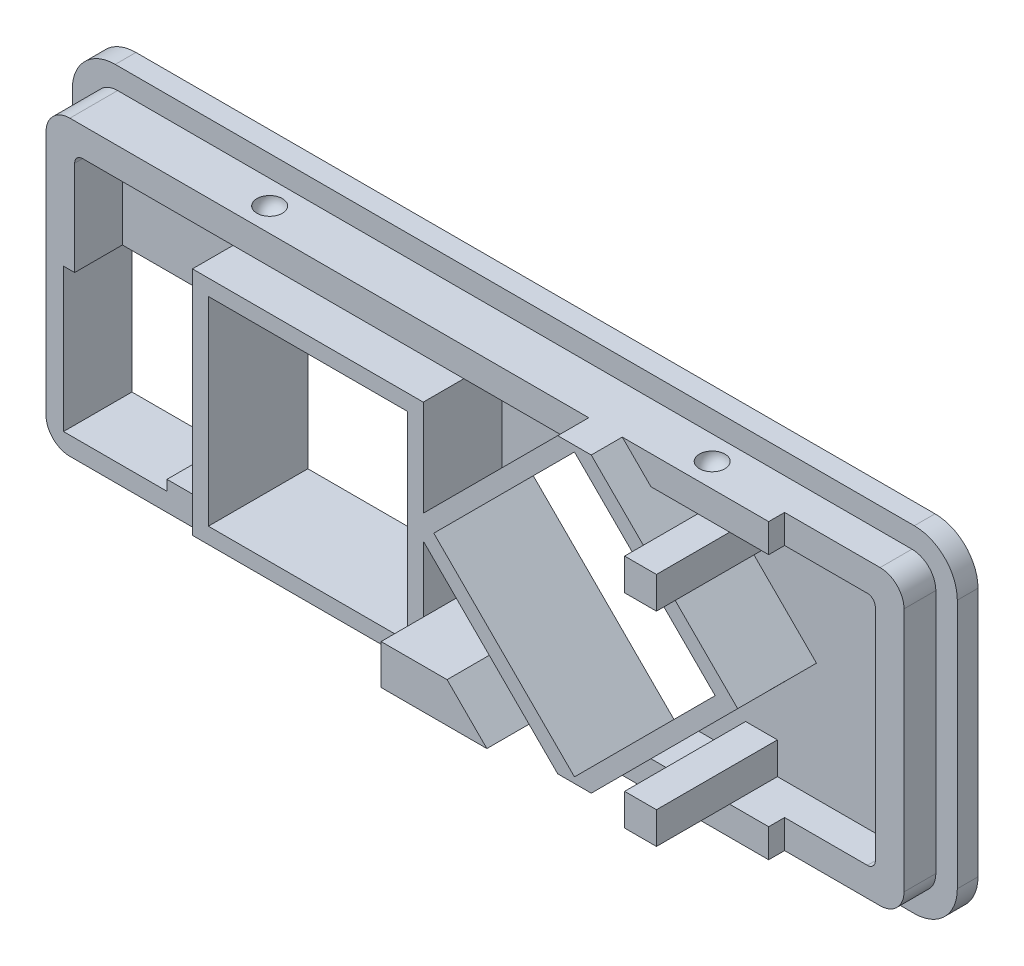
SolidWorks part; units mm, degrees
material "PLA"
ref_plane "Front Plane" through (0, 0, 0) normal (0, 0, 1) x (1, 0, 0)
ref_plane "Top Plane" through (0, 0, 0) normal (0, 1, 0) x (1, 0, 0)
ref_plane "Right Plane" through (0, 0, 0) normal (1, 0, 0) x (0, 0, -1)
sketch "Sketch1" plane through (0, 0, 0) normal (0, 0, 1) x (1, 0, 0)
  line L1 (2.7, 0) -> (52.9, 0)
  line L2 (0, 2.7) -> (0, 18.4)
  line L3 (2.7, 21.1) -> (52.9, 21.1)
  line L4 (55.6, 2.7) -> (55.6, 18.4)
  arc A0 (52.9, 0) -> (55.6, 2.7) centre (52.9, 2.7) ccw
  arc A1 (2.7, 0) -> (0, 2.7) centre (2.7, 2.7) cw
  arc A2 (0, 18.4) -> (2.7, 21.1) centre (2.7, 18.4) cw
  arc A3 (52.9, 21.1) -> (55.6, 18.4) centre (52.9, 18.4) cw
  point P9 (0, 0)
  dimension "D1" = 2.7
  dimension "D2" = 50.2
  dimension "D3" = 15.7
extrude "Boss-Extrude1" add sketch "Sketch1" along normal blind 1.3
sketch "Sketch4" plane through (0, 0, 1.3) normal (0, 0, 1) x (1, 0, 0)
  line L11 (54.25, 2.7) -> (54.25, 18.4)
  line L12 (52.9, 19.75) -> (2.7, 19.75)
  line L13 (1.35, 18.4) -> (1.35, 2.7)
  line L14 (2.7, 1.35) -> (52.9, 1.35)
  line L15 (54.25, 2.85) -> (54.25, 18.25)
  line L16 (52.75, 19.75) -> (2.85, 19.75)
  line L17 (1.35, 18.25) -> (1.35, 2.85)
  line L18 (2.85, 1.35) -> (52.75, 1.35)
  arc A4 (54.25, 18.25) -> (52.75, 19.75) centre (52.75, 18.25) ccw
  arc A5 (54.25, 2.85) -> (52.75, 1.35) centre (52.75, 2.85) cw
  arc A6 (1.35, 2.85) -> (2.85, 1.35) centre (2.85, 2.85) ccw
  arc A7 (2.85, 19.75) -> (1.35, 18.25) centre (2.85, 18.25) ccw
  arc A8 (52.9, 1.35) -> (54.25, 2.7) centre (52.9, 2.7) ccw
  arc A10 (54.25, 18.4) -> (52.9, 19.75) centre (52.9, 18.4) ccw
  arc A12 (2.7, 19.75) -> (1.35, 18.4) centre (2.7, 18.4) ccw
  arc A14 (1.35, 2.7) -> (2.7, 1.35) centre (2.7, 2.7) ccw
  dimension "D2" = 1.5
  dimension "D1" = 1.35
extrude "Boss-Extrude3" add sketch "Sketch4" along normal blind 3
sketch "Sketch5" plane through (0, 0, 4.3) normal (0, 0, 1) x (1, 0, 0)
  line L8 (52.45, 17.95) -> (3.15, 17.95)
  line L9 (3.15, 17.95) -> (3.15, 3.15)
  line L10 (3.15, 3.15) -> (52.45, 3.15)
  line L11 (52.45, 3.15) -> (52.45, 17.95)
  line L12 (51.95, 17.95) -> (3.65, 17.95)
  line L13 (3.15, 17.45) -> (3.15, 3.65)
  line L14 (3.65, 3.15) -> (51.95, 3.15)
  line L15 (52.45, 3.65) -> (52.45, 17.45)
  arc A4 (51.95, 3.15) -> (52.45, 3.65) centre (51.95, 3.65) ccw
  arc A5 (51.95, 17.95) -> (52.45, 17.45) centre (51.95, 17.45) cw
  arc A6 (3.65, 17.95) -> (3.15, 17.45) centre (3.65, 17.45) ccw
  arc A7 (3.15, 3.65) -> (3.65, 3.15) centre (3.65, 3.65) ccw
  dimension "D2" = 0.5
  dimension "D1" = 1.8
extrude "Cut-Extrude1" cut sketch "Sketch5" against normal blind 3
sketch "Sketch10" plane through (0, 19.75, 0) normal (0, 1, 0) x (1, 0, 0)
  line L0 (41.7, -2) -> (41.7, -3.6)
  line L1 (41.7, -3.6) -> (42.6713, -3.8888)
  line L3 (52.75, -1.3) -> (2.85, -1.3) construction
  line L4 (55.6, -1.3) -> (55.6, 0) construction
  arc A0 (41.7, -2) -> (41.7, -3.6) centre (41.7, -2.8) ccw
  dimension "D2" = 0.8
  dimension "D1" = 1.6
  dimension "D3" = 1.5
  dimension "D4" = 13.9
revolve "Cut-Revolve1" cut sketch "Sketch10" angle 360 about L0
ref_plane "Plane1" through (0, 10.55, 0) normal (0, -1, 0) x (-1, 0, 0)
mirror "Mirror1" about plane through (0, 10.55, 0) normal (0, -1, 0) of "Cut-Revolve1"
sketch "Sketch11" plane through (0, 0, 0) normal (0, 0, -1) x (-1, 0, 0)
  line L0 (0, 18.4) -> (0, 2.7) construction
  line L1 (-2.45, 2.5) -> (-8.95, 2.5)
  line L2 (-2.45, 2.5) -> (-2.45, 11.5)
  line L3 (-2.45, 11.5) -> (-8.95, 11.5)
  line L4 (-8.95, 2.5) -> (-8.95, 11.5)
  line L5 (-2.45, 2.5) -> (-8.95, 11.5) construction
  line L6 (-2.45, 11.5) -> (-8.95, 2.5) construction
  line L8 (-2.7, 0) -> (-52.9, 0) construction
  point P0 (-5.7, 7)
  dimension "D1" = 5.7
  dimension "D2" = 2.5
  dimension "D3" = 9
  dimension "D4" = 6.5
extrude "Cut-Extrude2" cut sketch "Sketch11" against normal blind 4.3
sketch "Sketch12" plane through (0, 0, 0) normal (0, 0, -1) x (-1, 0, 0)
  line L1 (-26, 16.35) -> (-13.5, 16.35)
  line L2 (-26, 16.35) -> (-26, 3.85)
  line L3 (-26, 3.85) -> (-13.5, 3.85)
  line L4 (-13.5, 16.35) -> (-13.5, 3.85)
  line L5 (-26, 16.35) -> (-13.5, 3.85) construction
  line L6 (-26, 3.85) -> (-13.5, 16.35) construction
  line L7 (-52.9, 21.1) -> (-2.7, 21.1) construction
  line L9 (0, 18.4) -> (0, 2.7) construction
  point P0 (-19.75, 10.1)
  dimension "D1" = 11
  dimension "D2" = 19.75
  dimension "D3" = 12.5
  dimension "D4" = 12.5
sketch "Sketch13" plane through (0, 0, 0) normal (0, 0, -1) x (-1, 0, 0)
  line L0 (-45.3388, 10.55) -> (-36.5, 1.7112)
  line L1 (-45.3388, 10.55) -> (-36.5, 19.3888)
  line L2 (-36.5, 1.7112) -> (-27.6612, 10.55)
  line L3 (-36.5, 19.3888) -> (-27.6612, 10.55)
  line L4 (-45.3388, 10.55) -> (-27.6612, 10.55) construction
  line L5 (-36.5, 1.7112) -> (-36.5, 19.3888) construction
  line L6 (-0.715, 10.55) -> (0.715, 10.55) construction
  line L7 (-52.9, 21.1) -> (-2.7, 21.1) construction
  line L10 (0, 18.4) -> (0, 2.7) construction
  point P1 (-36.5, 10.55)
  dimension "D1" = 0
  dimension "D2" = 10.55
  dimension "D3" = 12.5
  dimension "D5" = 36.5
extrude "Cut-Extrude4" cut sketch "Sketch12" against normal blind 1.3
sketch "Sketch17" plane through (0, 0, 0) normal (0, 0, -1) x (-1, 0, 0)
  line L8 (-13.5, 16.35) -> (-26, 16.35) construction
  line L9 (-27, 17.35) -> (-12.5, 17.35)
  line L10 (-27, 17.35) -> (-27, 2.85)
  line L11 (-27, 2.85) -> (-12.5, 2.85)
  line L12 (-12.5, 17.35) -> (-12.5, 2.85)
  line L13 (-26, 3.85) -> (-13.5, 3.85) construction
  line L14 (-13.5, 3.85) -> (-13.5, 16.35) construction
  line L15 (-26, 16.35) -> (-26, 3.85) construction
  line L17 (-13.5, 3.85) -> (-26, 3.85)
  line L18 (-13.5, 3.85) -> (-13.5, 16.35)
  line L19 (-13.5, 16.35) -> (-26, 16.35)
  line L20 (-26, 3.85) -> (-26, 16.35)
  dimension "D1" = 1
  dimension "D2" = 1
  dimension "D3" = 1
  dimension "D4" = 1
extrude "Boss-Extrude4" add sketch "Sketch17" against normal blind 6.25
extrude "Cut-Extrude5" cut sketch "Sketch13" against normal blind 4.3
sketch "Sketch18" plane through (0, 0, 0) normal (0, 0, -1) x (-1, 0, 0)
  line L18 (-36.5, 19.3888) -> (-45.3388, 10.55)
  line L19 (-45.3388, 10.55) -> (-36.5, 1.7112)
  line L20 (-36.5, 1.7112) -> (-27.6612, 10.55)
  line L21 (-27.6612, 10.55) -> (-36.5, 19.3888)
  line L22 (-46.753, 10.55) -> (-36.5, 0.297)
  line L23 (-36.5, 0.297) -> (-26.247, 10.55)
  line L24 (-26.247, 10.55) -> (-36.5, 20.803)
  line L25 (-36.5, 20.803) -> (-46.753, 10.55)
  line L26 (-46.753, 10.55) -> (-36.5, 0.297)
  line L27 (-36.5, 0.297) -> (-26.247, 10.55)
  line L28 (-26.247, 10.55) -> (-36.5, 20.803)
  line L29 (-36.5, 20.803) -> (-46.753, 10.55)
  dimension "D1" = 1
extrude "Boss-Extrude5" add sketch "Sketch18" against normal blind 6.25
sketch "Sketch20" plane through (0, 0, 4.3) normal (0, 0, 1) x (1, 0, 0)
  line L0 (35.447, 19.75) -> (37.553, 19.75)
  line L1 (35.447, 19.75) -> (2.85, 19.75) construction
  line L2 (52.75, 19.75) -> (37.553, 19.75) construction
  line L3 (37.553, 19.75) -> (36.5, 20.803)
  line L4 (36.5, 20.803) -> (35.447, 19.75)
extrude "Cut-Extrude6" cut sketch "Sketch20" against normal blind 3 and the other way blind 20
mirror "Mirror2" about plane through (0, 10.55, 0) normal (0, -1, 0) of "Cut-Extrude6"
sketch "Sketch21" plane through (0, 0, 0) normal (0, 0, -1) x (-1, 0, 0)
  line L0 (-52.9, 21.1) -> (-2.7, 21.1) construction
  line L1 (-30.25, 17.85) -> (-27.75, 17.85)
  line L2 (-30.25, 17.85) -> (-30.25, 15.35)
  line L3 (-30.25, 15.35) -> (-27.75, 15.35)
  line L4 (-27.75, 17.85) -> (-27.75, 15.35)
  line L5 (-30.25, 17.85) -> (-27.75, 15.35) construction
  line L6 (-30.25, 15.35) -> (-27.75, 17.85) construction
  line L7 (0, 18.4) -> (0, 2.7) construction
  point P0 (-29, 16.6)
  dimension "D1" = 4.5
  dimension "D2" = 2.5
  dimension "D3" = 2.5
  dimension "D4" = 29
extrude "Cut-Extrude7" cut sketch "Sketch21" against normal blind 10
ref_plane "Plane2" through (27.8, 0, 0) normal (-1, 0, 0) x (0, 0, 1)
mirror "Mirror3" about plane through (27.8, 0, 0) normal (-1, 0, 0) of "Mirror1", "Cut-Revolve1"
sketch "Sketch24" plane through (0, 0, 1.3) normal (0, 0, 1) x (1, 0, 0)
  line L0 (33.647, 3.15) -> (27, 3.15)
  line L2 (27, 3.15) -> (27, 5.65)
  line L4 (27, 5.65) -> (31.147, 5.65)
  line L5 (27, 9.797) -> (33.647, 3.15) construction
  line L6 (31.147, 5.65) -> (33.647, 3.15)
  line L7 (8.95, 3.15) -> (12.5, 3.15) construction
  line L8 (27, 11.303) -> (27, 17.35) construction
  dimension "D1" = 2.5
extrude "Boss-Extrude7" add sketch "Sketch24" along normal blind 7.6
sketch "Sketch25" plane through (0, 0, 1.3) normal (0, 0, 1) x (1, 0, 0)
  line L1 (44.3, 3.15) -> (42.3, 3.15)
  line L2 (44.3, 3.15) -> (44.3, 5.15)
  line L3 (44.3, 5.15) -> (42.3, 5.15)
  line L4 (42.3, 3.15) -> (42.3, 5.15)
  line L6 (39.353, 3.15) -> (51.95, 3.15) construction
  line L7 (52.45, 3.65) -> (52.45, 17.45) construction
  dimension "D1" = 8.15
  dimension "D2" = 2
  dimension "D3" = 2
extrude "Boss-Extrude8" add sketch "Sketch25" along normal blind 7.6
mirror "Mirror4" about plane through (0, 10.55, 0) normal (0, -1, 0) of "Boss-Extrude8"
sketch "Sketch23" plane through (0, 0, 1.3) normal (0, 0, 1) x (1, 0, 0)
  line L0 (-0.715, 10.55) -> (0.715, 10.55) construction
  line L1 (48.7, 3.15) -> (46.3, 3.15)
  line L2 (48.7, 3.15) -> (48.7, 17.95)
  line L3 (48.7, 17.95) -> (46.3, 17.95)
  line L4 (46.3, 3.15) -> (46.3, 17.95)
  line L5 (48.7, 3.15) -> (46.3, 17.95) construction
  line L6 (48.7, 17.95) -> (46.3, 3.15) construction
  line L7 (39.353, 3.15) -> (42.3, 3.15) construction
  line L8 (51.95, 17.95) -> (44.3, 17.95) construction
  line L9 (0, 18.4) -> (0, 2.7) construction
  point P0 (47.5, 10.55)
  dimension "D1" = 2.4
  dimension "D2" = 47.5
extrude "Boss-Extrude6" [suppressed] add sketch "Sketch23" along normal blind 3
sketch "Sketch27" plane through (54.25, 0, 0) normal (1, 0, 0) x (0, 0, -1)
  line L0 (-4.3, 2.85) -> (-4.3, 18.25) construction
  line L2 (-3.3, 19.75) -> (-4.3, 19.75)
  line L3 (-3.3, 19.75) -> (-3.3, 1.35)
  line L4 (-3.3, 1.35) -> (-4.3, 1.35)
  line L5 (-4.3, 19.75) -> (-4.3, 1.35)
  line L6 (-3.3, 19.75) -> (-4.3, 1.35) construction
  line L7 (-3.3, 1.35) -> (-4.3, 19.75) construction
  point P2 (-4.3, 10.55)
  point P3 (-3.8, 10.55)
  dimension "D1" = 1
  dimension "D2" = 18.4
extrude "Cut-Extrude8" cut sketch "Sketch27" against normal blind 7.5
equation "\"OutterLength\"= 55.6mm"
equation "\"OutterWidth\"= 21.1mm"
equation "\"EdgeRadius\"= 2.7mm"
equation "\"LipOffset\"= 1.35mm"
equation "\"LipHeight\"= 3mm"
equation "\"LipThickness\"= 1.8mm"
equation "\"LatchRadius\"= 0.8mm"
equation "\"D2@Sketch1\"=\"OutterLength\"-\"EdgeRadius\"*2"
equation "\"D3@Sketch1\"=\"OutterWidth\"-\"EdgeRadius\"*2"
equation "\"D1@Sketch1\"=\"EdgeRadius\""
equation "\"D1@Sketch4\"=\"LipOffset\""
equation "\"LipRadius\"= 1.5mm"
equation "\"D2@Sketch4\"=\"LipRadius\""
equation "\"D1@Sketch5\"=\"LipThickness\""
equation "\"D1@Boss-Extrude3\"=\"LipHeight\""
equation "\"D1@Cut-Extrude1\"=\"LipHeight\""
equation "\"D2@Sketch10\"=\"LatchRadius\""
equation "\"D1@Sketch10\"=\"LatchRadius\"*2"
equation "\"D3@Sketch10\"=\"LipHeight\"/2"
equation "\"D1@Cut-Extrude2\"=\"LipHeight\"+\"WallThickness\""
equation "\"WallThickness\"= 1.3mm"
equation "\"D1@Boss-Extrude1\"=\"WallThickness\""
equation "\"D1@Cut-Extrude4\"=\"WallThickness\""
equation "\"D1@Cut-Extrude5\"=\"WallThickness\"+\"LipHeight\""
equation "\"D1@Cut-Extrude6\"=\"LipHeight\""
equation "\"D2@Cut-Extrude6\"=20mm"
equation "\"D4@Sketch10\"=\"OutterLength\"/4"
equation "\"D2@Sketch13\"=\"OutterWidth\"/2"
